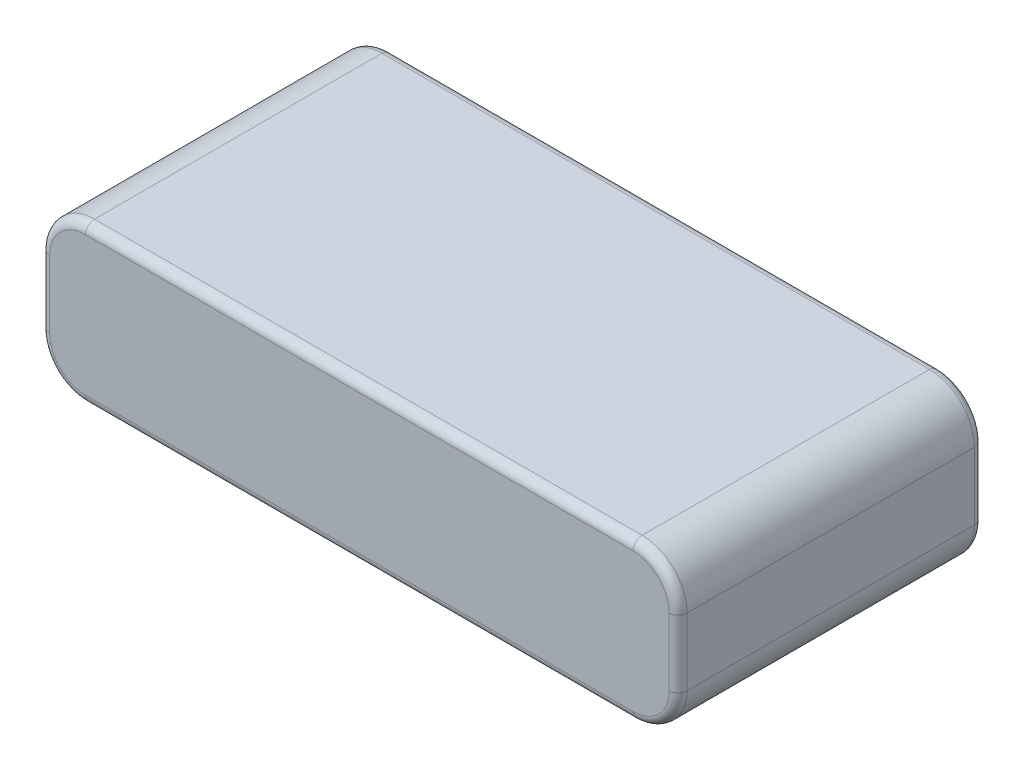
SolidWorks part; units mm, degrees
ref_plane "Front Plane" through (0, 0, 0) normal (0, 0, 1) x (1, 0, 0)
ref_plane "Top Plane" through (0, 0, 0) normal (0, 1, 0) x (1, 0, 0)
ref_plane "Right Plane" through (0, 0, 0) normal (1, 0, 0) x (0, 0, -1)
sketch "Sketch1" plane through (0, 0, 0) normal (0, 1, 0) x (1, 0, 0)
  line L1 (-35.5, 17) -> (35.5, 17)
  line L2 (-35.5, 17) -> (-35.5, -17)
  line L3 (-35.5, -17) -> (35.5, -17)
  line L4 (35.5, 17) -> (35.5, -17)
  line L5 (-35.5, 17) -> (35.5, -17) construction
  line L6 (-35.5, -17) -> (35.5, 17) construction
  point P0 (0, 0)
  dimension "D1" = 71
  dimension "D2" = 34
extrude "Boss-Extrude1" add sketch "Sketch1" along normal blind 17.5
fillet "Fillet1" radius 5 4 edges at (-35.5, 0, 0) (35.5, 0, 0) (35.5, 17.5, 0) (-35.5, 17.5, 0)
fillet "Fillet2" radius 1 16 edges at (-34.0355, 16.0355, 17) (0, 17.5, 17) (34.0355, 16.0355, 17) (35.5, 8.75, 17) (34.0355, 1.4645, 17) (0, 0, 17) (-34.0355, 1.4645, 17) (-35.5, 8.75, 17) (34.0355, 1.4645, -17) (35.5, 8.75, -17) (34.0355, 16.0355, -17) (0, 17.5, -17) (-34.0355, 16.0355, -17) (-35.5, 8.75, -17) (-34.0355, 1.4645, -17) (0, 0, -17)
